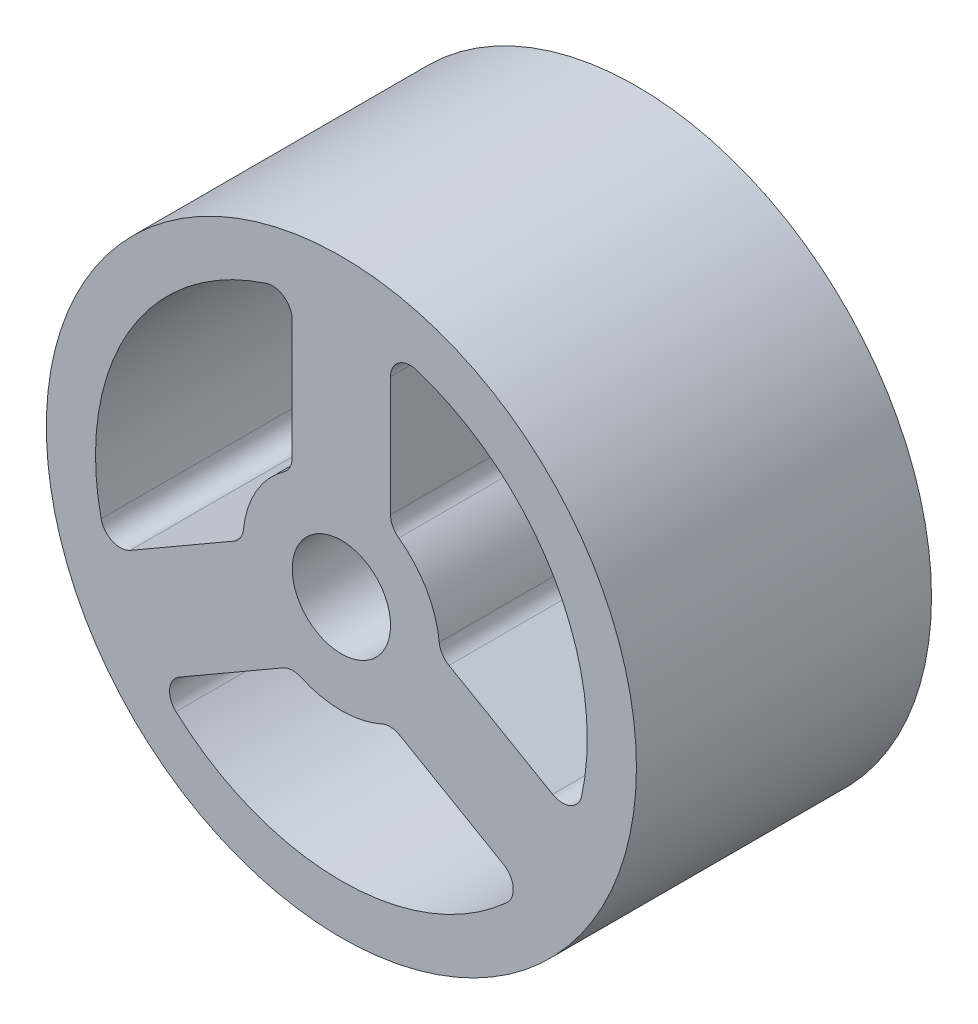
SolidWorks part; units mm, degrees
ref_plane "Front Plane" through (0, 0, 0) normal (0, 0, 1) x (1, 0, 0)
ref_plane "Top Plane" through (0, 0, 0) normal (0, 1, 0) x (1, 0, 0)
ref_plane "Right Plane" through (0, 0, 0) normal (1, 0, 0) x (0, 0, -1)
sketch "Sketch1" plane through (0, 0, 0) normal (0, 0, 1) x (1, 0, 0)
  line L0 (0, 36.2338) -> (0, -37.2648) construction
  line L1 (-45.3883, 0) -> (37.46, 0) construction
  line L2 (-5, 21.9089) -> (-5, 9.7468)
  line L3 (5, 21.9089) -> (5, 9.7468)
  line L4 (21.4737, -6.6243) -> (10.941, -0.5433)
  line L5 (16.4737, -15.2846) -> (5.941, -9.2035)
  line L7 (-16.4737, -15.2846) -> (-5.941, -9.2035)
  line L8 (-21.4737, -6.6243) -> (-10.941, -0.5433)
  line L9 (-31.3794, -18.1169) -> (32.2723, 18.6324) construction
  line L10 (31.3794, -18.1169) -> (-32.2723, 18.6324) construction
  circle A0 centre (0, 0) radius 30
  circle A1 centre (0, 0) radius 25
  circle A2 centre (0, 0) radius 10
  circle A3 centre (0, 0) radius 5
  arc A4 (-7.6087, 23.814) -> (-5, 21.9089) centre (-7, 21.9089) cw
  arc A5 (-5, 9.7468) -> (-5.8333, 8.1223) centre (-7, 9.7468) cw
  arc A6 (5, 9.7468) -> (5.8333, 8.1223) centre (7, 9.7468) ccw
  arc A7 (7.6087, 23.814) -> (5, 21.9089) centre (7, 21.9089) ccw
  arc A8 (16.8192, -18.4963) -> (16.4737, -15.2846) centre (15.4737, -17.0166) ccw
  arc A9 (24.4279, -5.3177) -> (21.4737, -6.6243) centre (22.4737, -4.8923) cw
  arc A10 (10.941, -0.5433) -> (9.9508, 0.9907) centre (11.941, 1.1888) cw
  arc A11 (5.941, -9.2035) -> (4.1175, -9.113) centre (4.941, -10.9356) ccw
  circle A12 centre (0, 0) radius 25
  arc A13 (-24.4279, -5.3177) -> (-21.4737, -6.6243) centre (-22.4737, -4.8923) ccw
  arc A14 (-16.8192, -18.4963) -> (-16.4737, -15.2846) centre (-15.4737, -17.0166) cw
  arc A15 (-5.941, -9.2035) -> (-4.1175, -9.113) centre (-4.941, -10.9356) cw
  arc A16 (-10.941, -0.5433) -> (-9.9508, 0.9907) centre (-11.941, 1.1888) ccw
  circle A17 centre (0, 0) radius 25
  point P55 (0, 0)
  dimension "D1" = 50
  dimension "D2" = 60
  dimension "D3" = 20
  dimension "D4" = 10
  dimension "D7" = 2
  dimension "2" = 2
  dimension "D8" = 2
  dimension "D9" = 2
  dimension "D5" = 5
  dimension "D6" = 5
  dimension "D11" = 60
  dimension "D10" = 3
extrude "Boss-Extrude1" add sketch "Sketch1" along normal blind 30 contours A0 A1 A12 | A7 A1 A4 L2 A5 A2 A6 L3 | A16 L8 A13 A12 A14 L7 A15 A2 | A11 L5 A8 A1 A9 L4 A10 A2 | A2 A3
